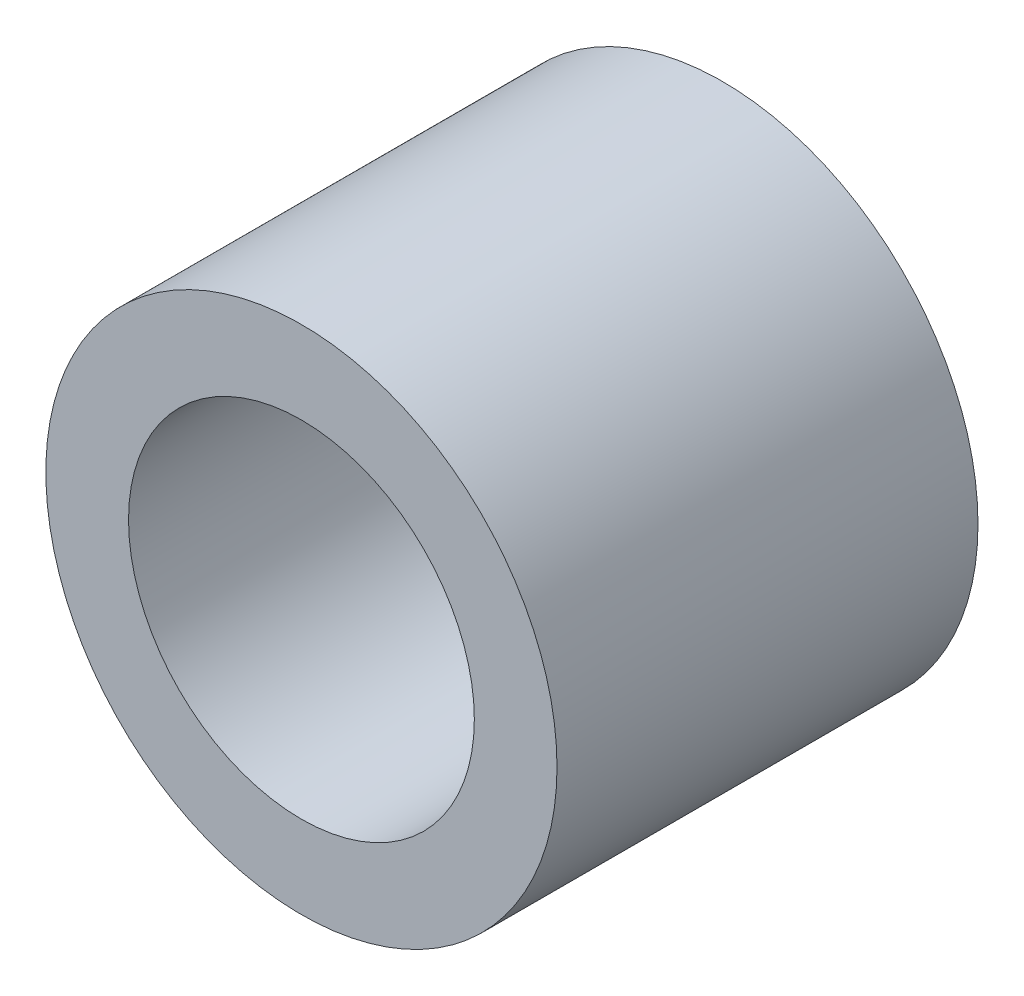
SolidWorks part; units mm, degrees
material "Alliage 1060"
ref_plane "Plan de face" through (0, 0, 0) normal (0, 0, 1) x (1, 0, 0)
ref_plane "Plan de dessus" through (0, 0, 0) normal (0, 1, 0) x (1, 0, 0)
ref_plane "Plan de droite" through (0, 0, 0) normal (1, 0, 0) x (0, 0, -1)
sketch "Esquisse1" plane through (0, 0, 0) normal (0, 0, 1) x (1, 0, 0)
  circle A0 centre (0, 0) radius 2.3
  circle A1 centre (0, 0) radius 3.4
  dimension "D1" = 4.6
  dimension "D2" = 6.8
  dimension "D3" = 1.1
extrude "Boss.-Extru.1" add sketch "Esquisse1" along normal mid plane 5.6
